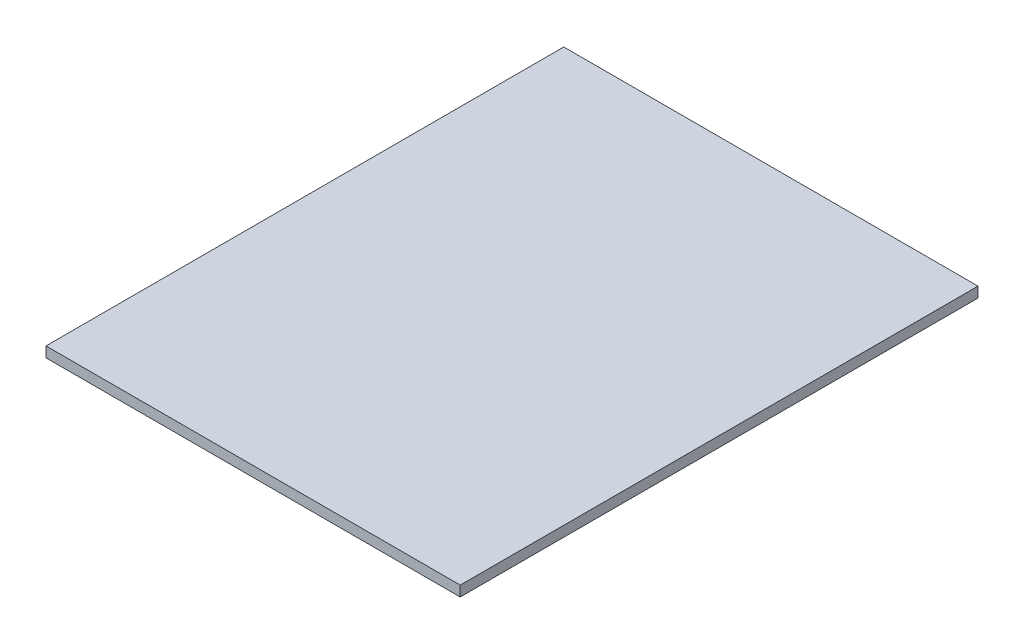
SolidWorks part; units mm, degrees
ref_plane "Front Plane" through (0, 0, 0) normal (0, 0, 1) x (1, 0, 0)
ref_plane "Top Plane" through (0, 0, 0) normal (0, 1, 0) x (1, 0, 0)
ref_plane "Right Plane" through (0, 0, 0) normal (1, 0, 0) x (0, 0, -1)
sketch "Sketch1" plane through (0, 0, 0) normal (0, 1, 0) x (1, 0, 0)
  line L1 (100, -125) -> (-100, -125)
  line L2 (100, -125) -> (100, 125)
  line L3 (100, 125) -> (-100, 125)
  line L4 (-100, -125) -> (-100, 125)
  line L5 (100, -125) -> (-100, 125) construction
  line L6 (100, 125) -> (-100, -125) construction
  point P0 (0, 0)
  dimension "D1" = 250
  dimension "D2" = 200
extrude "Boss-Extrude1" add sketch "Sketch1" along normal blind 5
